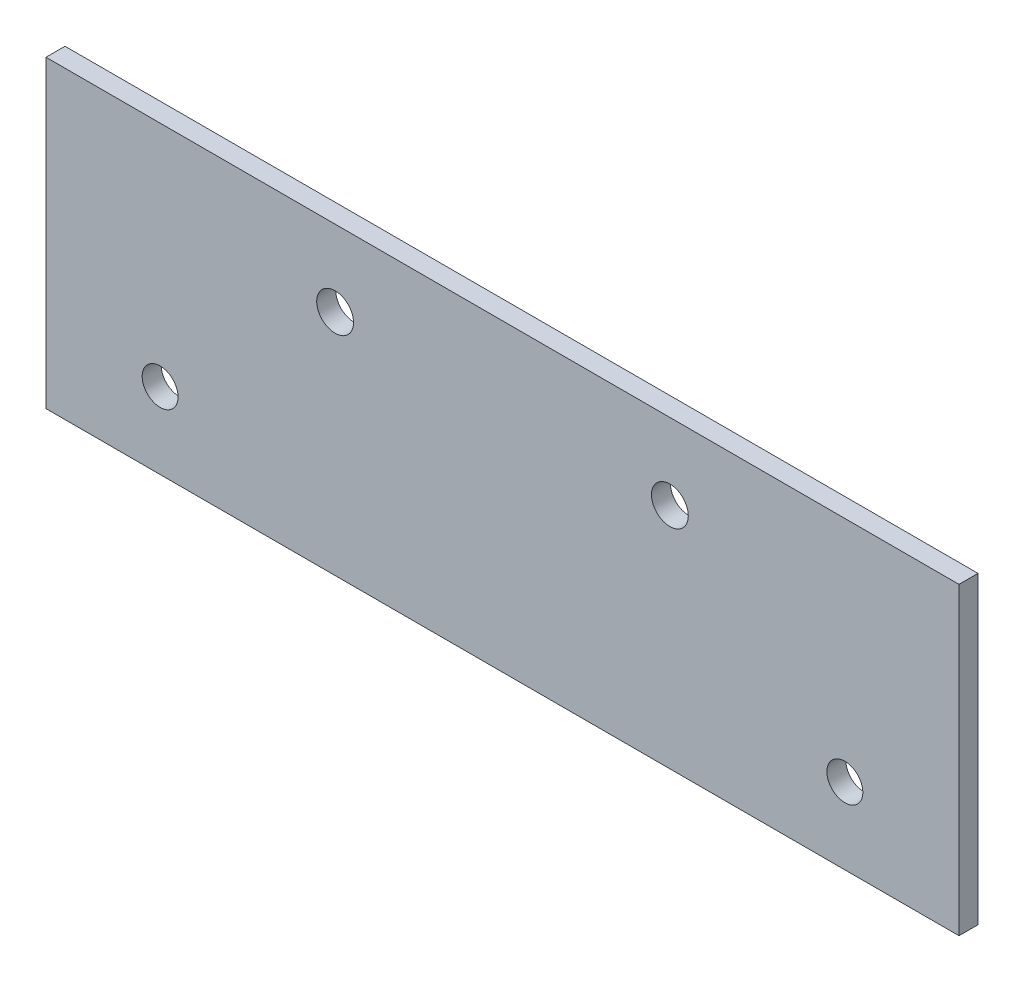
SolidWorks part; units mm, degrees
material "6061-T6 (SS)"
ref_plane "Front Plane" through (0, 0, 0) normal (0, 0, 1) x (1, 0, 0)
ref_plane "Top Plane" through (0, 0, 0) normal (0, 1, 0) x (1, 0, 0)
ref_plane "Right Plane" through (0, 0, 0) normal (1, 0, 0) x (0, 0, -1)
sketch "Sketch1" plane through (0, 0, 0) normal (0, 0, 1) x (1, 0, 0)
  line L0 (-27.94, 25.4) -> (27.94, 25.4) construction
  line L1 (-57.15, 0) -> (57.15, 0) construction
  line L2 (0, 25.4) -> (0, 0) construction
  line L4 (-76.2, -12.7) -> (76.2, -12.7)
  line L5 (-76.2, -12.7) -> (-76.2, 38.1)
  line L6 (-76.2, 38.1) -> (76.2, 38.1)
  line L7 (76.2, -12.7) -> (76.2, 38.1)
  circle A2 centre (-27.94, 25.4) radius 3.0734
  circle A3 centre (27.94, 25.4) radius 3.0734
  circle A6 centre (-57.15, 0) radius 3
  circle A7 centre (57.15, 0) radius 3
  dimension "D1" = 6.1468
  dimension "D2" = 6
  dimension "D3" = 6.1468
  dimension "D4" = 6
  dimension "D5" = 55.88
  dimension "D6" = 114.3
  dimension "D7" = 25.4
  dimension "D8" = 50.8
  dimension "D9" = 152.4
  dimension "D10" = 12.7
  dimension "D11" = 76.2
extrude "Boss-Extrude1" add sketch "Sketch1" along normal blind 3.175
